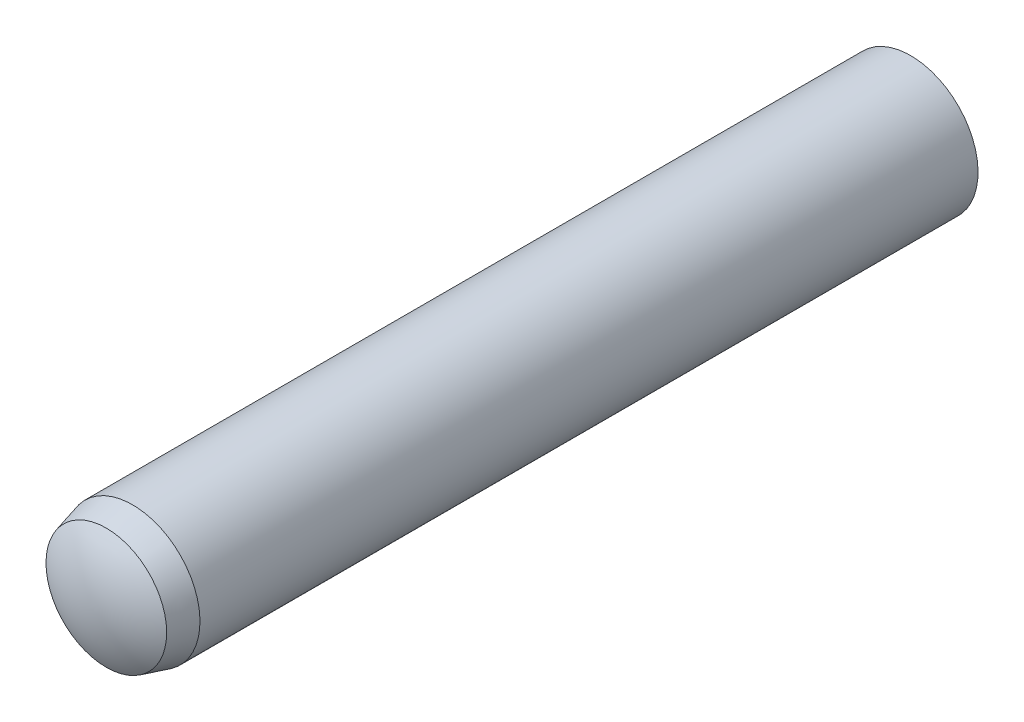
SolidWorks part; units mm, degrees
ref_plane "Front Plane" through (0, 0, 0) normal (0, 0, 1) x (1, 0, 0)
ref_plane "Top Plane" through (0, 0, 0) normal (0, 1, 0) x (1, 0, 0)
ref_plane "Right Plane" through (0, 0, 0) normal (1, 0, 0) x (0, 0, -1)
sketch "Sketch1" plane through (0, 0, 0) normal (0, 0, 1) x (1, 0, 0)
  circle A0 centre (0, 0) radius 4
  point P3 (0, 4)
  dimension "Diameter" = 8
sketch "Sketch2" plane through (0, 0, 0) normal (1, 0, 0) x (0, 0, -1)
  line L0 (-25, 0) -> (25, 0) construction
  line L1 (-25, 0) -> (-25, 4) construction
  line L2 (-25, 4) -> (25, 4)
  line L3 (25, 4) -> (25, 0) construction
  line L4 (-23.96, 3.582) -> (-22.4, 4)
  arc A0 (-25, 0) -> (-23.96, 3.582) centre (-18.3114, 0) cw
  arc A1 (25, 0) -> (23.8, 4) centre (17.7333, 0) ccw
  point P2 (0, 0)
  point P11 (-17, 0)
  point P13 (17, 0)
  dimension "Length" = 50
  dimension "D1" = 15
  dimension "D2" = 1.2
  dimension "D3" = 2.6
  dimension "D4" = 1.56
  dimension "D5" = 8
  dimension "D6" = 8
sketch "Sketch3" plane through (0, 0, 0) normal (1, 0, 0) x (0, 0, -1)
  line L0 (-25, 0) -> (25, 0) construction
  line L1 (-23.96, 3.582) -> (-22.4, 4) construction
  line L2 (-25, 0) -> (25, 0)
  line L3 (-23.96, 3.582) -> (-22.4, 4)
  line L4 (-22.4, 4) -> (23.8, 4)
  arc A0 (25, 0) -> (23.8, 4) centre (17.7333, 0) ccw construction
  arc A1 (-23.96, 3.582) -> (-25, 0) centre (-18.3114, 0) ccw construction
  arc A2 (25, 0) -> (23.8, 4) centre (17.7333, 0) ccw
  arc A3 (-23.96, 3.582) -> (-25, 0) centre (-18.3114, 0) ccw
revolve "Revolve1" add sketch "Sketch3" angle 360 about L2
equation "\"D2@Sketch2\" = \"Diameter@Sketch1\" * .15"
equation "\"D3@Sketch2\" = \"Diameter@Sketch1\" * .325"
equation "\"D4@Sketch2\" = \"D3@Sketch2\" * .6"
equation "\"D5@Sketch2\"=\"Diameter@Sketch1\""
equation "\"D6@Sketch2\"=\"D5@sketch2\""
